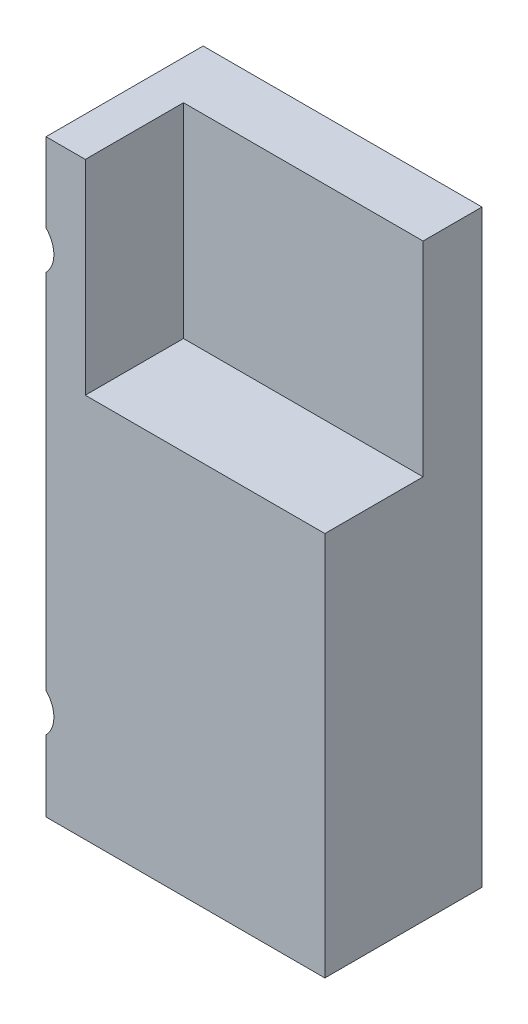
SolidWorks part; units mm, degrees
ref_plane "Front Plane" through (0, 0, 0) normal (0, 0, 1) x (1, 0, 0)
ref_plane "Top Plane" through (0, 0, 0) normal (0, 1, 0) x (1, 0, 0)
ref_plane "Right Plane" through (0, 0, 0) normal (1, 0, 0) x (0, 0, -1)
sketch "Sketch1" plane through (0, 0, 0) normal (0, 0, 1) x (1, 0, 0)
  line L1 (-7.0643, 9.6979) -> (10.9697, 9.6979)
  line L2 (-7.0643, 9.6979) -> (-7.0643, -28.4021)
  line L3 (-7.0643, -28.4021) -> (10.9697, -28.4021)
  line L4 (10.9697, 9.6979) -> (10.9697, -28.4021)
  dimension "D1" = 38.1
  dimension "D2" = 18.034
extrude "Boss-Extrude1" add sketch "Sketch1" along normal blind 3.81 contours L2 L1 L4 L3
sketch "Sketch2" plane through (0, 0, 3.81) normal (0, 0, 1) x (1, 0, 0)
  line L18 (-7.0643, -28.4021) -> (-4.5243, -28.4021)
  line L19 (-7.0643, -28.4021) -> (-7.0643, 9.6979)
  line L20 (-7.0643, 9.6979) -> (-4.5243, 9.6979)
  line L21 (-4.5243, -28.4021) -> (-4.5243, 9.6979)
  line L22 (10.9697, -28.4021) -> (8.4297, -28.4021)
  line L23 (10.9697, -28.4021) -> (10.9697, -3.5101)
  line L24 (10.9697, -3.5101) -> (8.4297, -3.5101)
  line L25 (8.4297, -28.4021) -> (8.4297, -3.5101)
  dimension "D1" = 38.1
  dimension "D2" = 2.54
  dimension "D3" = 2.54
  dimension "D4" = 24.892
extrude "Boss-Extrude2" add sketch "Sketch2" along normal blind 6.35
sketch "Sketch4" plane through (0, 0, 3.81) normal (0, 0, 1) x (1, 0, 0)
  line L0 (-4.5243, -28.4021) -> (-4.5243, 9.6979) construction
  line L1 (8.4297, -3.5101) -> (-4.5243, -3.5101)
  line L2 (8.4297, -3.5101) -> (8.4297, -6.6894)
  line L3 (8.4297, -6.6894) -> (-4.5243, -6.6894)
  line L4 (-4.5243, -3.5101) -> (-4.5243, -6.6894)
extrude "Boss-Extrude4" add sketch "Sketch4" along normal blind 6.35
sketch "Sketch6" plane through (0, 0, 0) normal (0, 0, 1) x (1, 0, 0)
  line L2 (-4.5243, -3.5101) -> (-4.5243, 9.6979) construction
  line L3 (-7.0643, 9.6979) -> (10.9697, 9.6979) construction
  circle A0 centre (-8.3343, 3.3479) radius 1.778
  circle A1 centre (-8.3343, -22.5601) radius 1.778
  dimension "D1" = 3.556
  dimension "D3" = 6.35
  dimension "D4" = 32.258
  dimension "D2" = 3.81
extrude "Cut-Extrude1" cut sketch "Sketch6" along normal blind 12.192
sketch "Sketch7" plane through (0, 0, 3.81) normal (0, 0, 1) x (1, 0, 0)
  line L1 (-4.5243, -6.6894) -> (8.4297, -6.6894)
  line L2 (-4.5243, -6.6894) -> (-4.5243, -28.4021)
  line L3 (-4.5243, -28.4021) -> (8.4297, -28.4021)
  line L4 (8.4297, -6.6894) -> (8.4297, -28.4021)
extrude "Boss-Extrude5" add sketch "Sketch7" along normal blind 6.35
